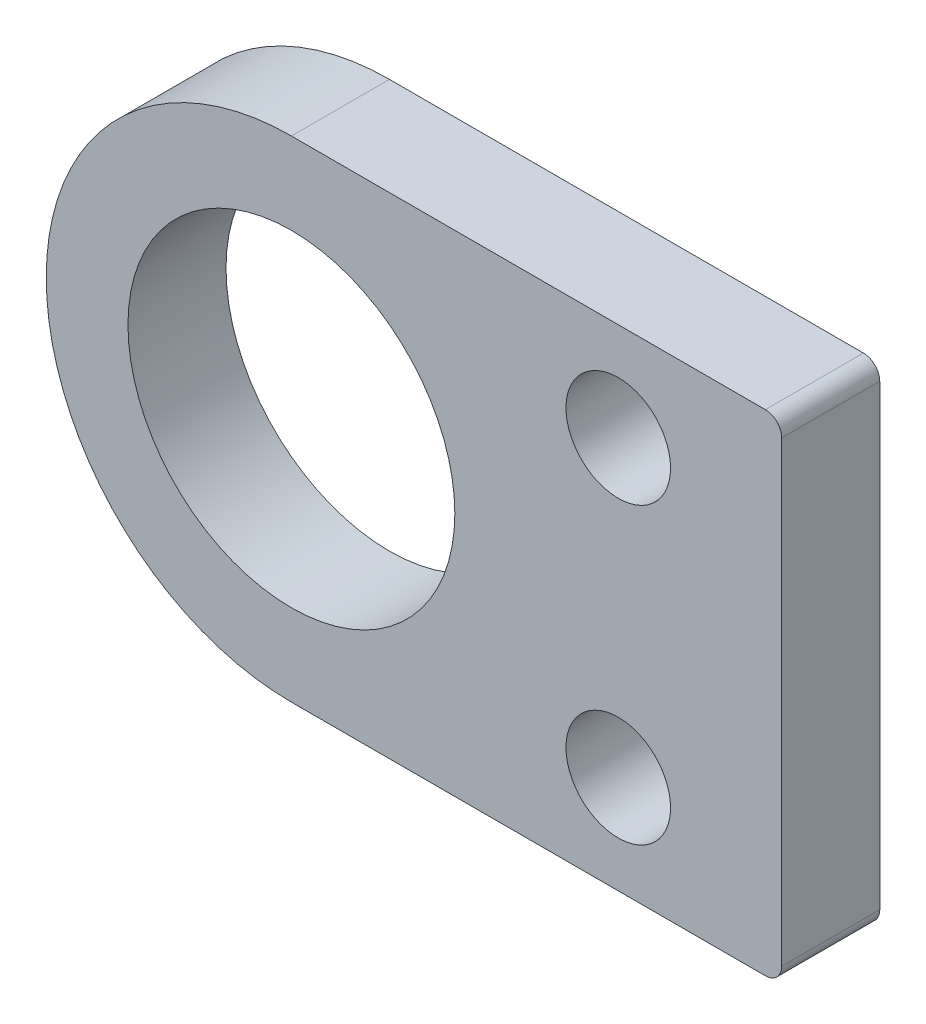
SolidWorks part; units mm, degrees
material "5052-H34"
ref_plane "正面" through (0, 0, 0) normal (0, 0, 1) x (1, 0, 0)
ref_plane "平面" through (0, 0, 0) normal (0, 1, 0) x (1, 0, 0)
ref_plane "右側面" through (0, 0, 0) normal (1, 0, 0) x (0, 0, -1)
sketch "ｽｹｯﾁ1" plane through (0, 0, 0) normal (0, 0, 1) x (1, 0, 0)
  line L0 (0, 0) -> (15, 0) construction
  line L1 (0, 7.5) -> (15, 7.5)
  line L2 (0, -7.5) -> (15, -7.5)
  line L3 (15, 7.5) -> (15, -7.5)
  arc A0 (0, 7.5) -> (0, -7.5) centre (0, 0) ccw
  circle A1 centre (0, 0) radius 5
  circle A2 centre (10, 4.5) radius 1.6
  circle A3 centre (10, -4.5) radius 1.6
  point P3 (24.9613, 0)
  dimension "D1" = 7.5
  dimension "D3" = 10
  dimension "D4" = 3.2
  dimension "D5" = 5
  dimension "D6" = 3
  dimension "D2" = 15
extrude "ﾎﾞｽ - 押し出し1" add sketch "ｽｹｯﾁ1" along normal blind 3
fillet "ﾌｨﾚｯﾄ1" radius 0.5 2 edges at (15, -7.5, 1.5) (15, 7.5, 1.5)
